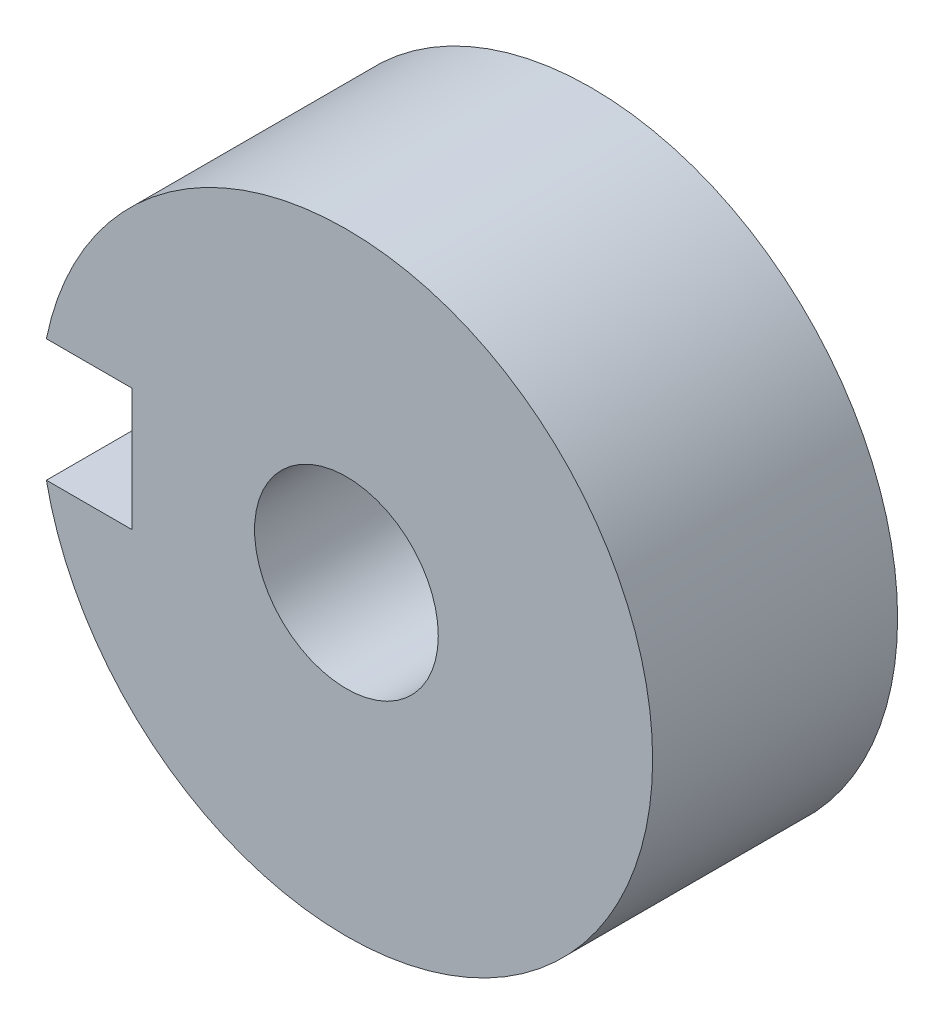
SolidWorks part; units mm, degrees
ref_plane "Front Plane" through (0, 0, 0) normal (0, 0, 1) x (1, 0, 0)
ref_plane "Top Plane" through (0, 0, 0) normal (0, 1, 0) x (1, 0, 0)
ref_plane "Right Plane" through (0, 0, 0) normal (1, 0, 0) x (0, 0, -1)
sketch "Sketch1" plane through (0, 0, 0) normal (0, 0, 1) x (1, 0, 0)
  circle A0 centre (0, 0) radius 1.5
  circle A1 centre (0, 0) radius 5
  dimension "D1" = 10
  dimension "D2" = 3
extrude "Boss-Extrude1" add sketch "Sketch1" along normal blind 4
sketch "Sketch2" plane through (0, 0, 4) normal (0, 0, 1) x (1, 0, 0)
  line L1 (-6.5, 1) -> (-3.5, 1)
  line L2 (-6.5, 1) -> (-6.5, -1)
  line L3 (-6.5, -1) -> (-3.5, -1)
  line L4 (-3.5, 1) -> (-3.5, -1)
  line L5 (-6.5, 1) -> (-3.5, -1) construction
  line L6 (-6.5, -1) -> (-3.5, 1) construction
  circle A0 centre (0, 0) radius 5 construction
  point P0 (-5, 0)
  dimension "D1" = 2
  dimension "D2" = 3
extrude "Cut-Extrude1" cut sketch "Sketch2" against normal blind 10
